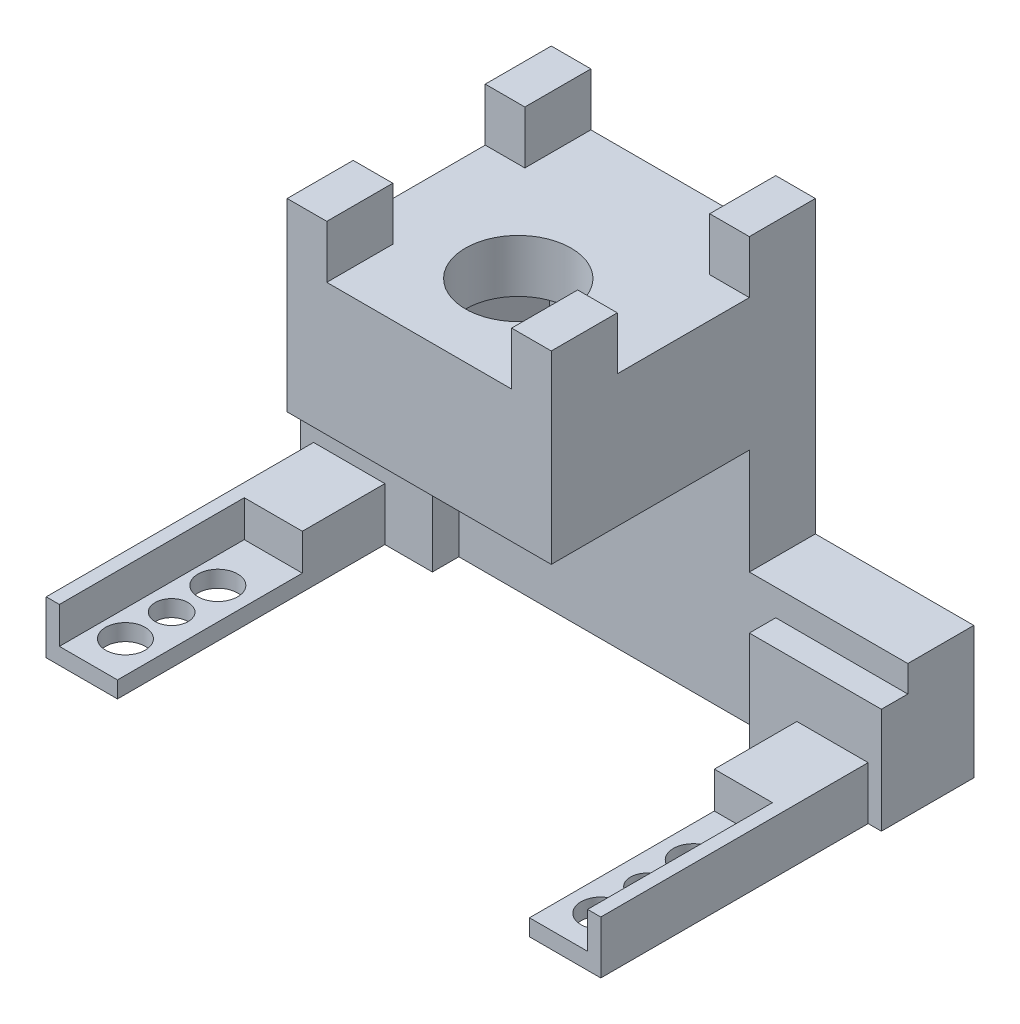
SolidWorks part; units mm, degrees
ref_plane "Front Plane" through (0, 0, 0) normal (0, 0, 1) x (1, 0, 0)
ref_plane "Top Plane" through (0, 0, 0) normal (0, 1, 0) x (1, 0, 0)
ref_plane "Right Plane" through (0, 0, 0) normal (1, 0, 0) x (0, 0, -1)
sketch "Sketch1" plane through (0, 0, 0) normal (0, 0, 1) x (1, 0, 0)
  line L0 (0, 0) -> (44, 0)
  line L5 (44, 0) -> (44, 10)
  line L6 (44, 10) -> (32, 10)
  line L7 (32, 10) -> (32, 28)
  line L8 (32, 28) -> (12, 28)
  line L9 (12, 28) -> (12, 10)
  line L10 (12, 10) -> (0, 10)
  line L11 (0, 10) -> (0, 0)
  point P6 (22, 28)
  point P10 (22, 0)
  dimension "D1" = 20
  dimension "D2" = 44
  dimension "D3" = 10
  dimension "D4" = 18
extrude "Boss-Extrude1" add sketch "Sketch1" along normal blind 5
sketch "Sketch2" plane through (0, 0, 5) normal (0, 0, 1) x (1, 0, 0)
  line L1 (44, 0) -> (34, 0)
  line L2 (44, 0) -> (44, 8)
  line L3 (44, 8) -> (34, 8)
  line L4 (34, 0) -> (34, 8)
  line L5 (0, 0) -> (10, 0)
  line L6 (0, 0) -> (0, 8)
  line L7 (0, 8) -> (10, 8)
  line L8 (10, 0) -> (10, 8)
  dimension "D1" = 10
  dimension "D2" = 8
extrude "Boss-Extrude2" add sketch "Sketch2" along normal blind 2
sketch "Sketch3" plane through (0, 0, 7) normal (0, 0, 1) x (1, 0, 0)
  line L0 (34, 0) -> (44, 0) construction
  line L1 (43, 0) -> (37.6, 0)
  line L2 (43, 0) -> (43, 4)
  line L3 (43, 4) -> (37.6, 4)
  line L4 (37.6, 0) -> (37.6, 4)
  line L5 (0, 0) -> (10, 0) construction
  line L6 (6.4, 0) -> (1, 0)
  line L7 (6.4, 0) -> (6.4, 4)
  line L8 (6.4, 4) -> (1, 4)
  line L9 (1, 0) -> (1, 4)
  line L11 (37.6, 4) -> (42, 4)
  line L12 (37.6, 4) -> (37.6, 1.25)
  line L13 (37.6, 1.25) -> (42, 1.25)
  line L14 (44, 0) -> (44, 8)
  line L15 (44, 8) -> (34, 8)
  line L16 (34, 8) -> (34, 0)
  line L17 (34, 0) -> (44, 0)
  line L18 (44, 0) -> (44, 8)
  line L19 (44, 8) -> (34, 8)
  line L20 (34, 8) -> (34, 0)
  line L21 (34, 0) -> (44, 0)
  line L22 (0, 8) -> (0, 0)
  line L23 (0, 0) -> (10, 0)
  line L24 (10, 0) -> (10, 8)
  line L25 (10, 8) -> (0, 8)
  line L26 (0, 8) -> (0, 0)
  line L27 (0, 0) -> (10, 0)
  line L28 (10, 0) -> (10, 8)
  line L29 (10, 8) -> (0, 8)
  line L30 (42, 4) -> (42, 1.25)
  line L31 (6.4, 4) -> (2, 4)
  line L32 (6.4, 4) -> (6.4, 1.25)
  line L33 (6.4, 1.25) -> (2, 1.25)
  line L34 (2, 4) -> (2, 1.25)
  line M18 (34, 0) -> (44, 0)
  dimension "D3" = 1
  dimension "D4" = 1
  dimension "D5" = 4
  dimension "D6" = 5.4
  dimension "D7" = 1.25
  dimension "D8" = 1
  dimension "D1" = 0
  dimension "D2" = 0
extrude "Boss-Extrude3" add sketch "Sketch3" along normal blind 20.25 contours L9 L6 L7 L8 | L3 L30 L13 L4 L2 M18
sketch "Sketch4" plane through (0, 1.25, 0) normal (0, 1, 0) x (1, 0, 0)
  line L4 (6.4, -7) -> (2, -7)
  line L5 (2, -7) -> (2, -27.25)
  line L6 (2, -27.25) -> (6.4, -27.25)
  line L7 (6.4, -27.25) -> (6.4, -7)
  line L8 (6.4, -7) -> (2, -7)
  line L9 (2, -7) -> (2, -27.25)
  line L10 (2, -27.25) -> (6.4, -27.25)
  line L11 (6.4, -27.25) -> (6.4, -7)
  line L16 (42, -7) -> (37.6, -7)
  line L17 (37.6, -7) -> (37.6, -27.25)
  line L18 (37.6, -27.25) -> (42, -27.25)
  line L19 (42, -27.25) -> (42, -7)
  line L20 (42, -7) -> (37.6, -7)
  line L21 (37.6, -7) -> (37.6, -27.25)
  line L22 (37.6, -27.25) -> (42, -27.25)
  line L23 (42, -27.25) -> (42, -7)
  circle A0 centre (4, -24.25) radius 1.5
  circle A1 centre (4, -20.75) radius 1.25
  circle A2 centre (4, -17.25) radius 1.5
  circle A3 centre (40, -17.25) radius 1.5
  circle A4 centre (40, -20.75) radius 1.25
  circle A5 centre (40, -24.25) radius 1.5
  dimension "D1" = 0
  dimension "D2" = 0
  dimension "D4" = 3
  dimension "D5" = 2.5
  dimension "D3" = 2.4
  dimension "D6" = 7
  dimension "D7" = 3.5
  dimension "D8" = 3
  dimension "D9" = 2.4
extrude "Cut-Extrude1" cut sketch "Sketch4" against normal through all contours A4 | A5 | A0 | A2 | A1 | A3
sketch "Sketch6" plane through (0, 0, 7) normal (0, 0, 1) x (1, 0, 0)
  line L0 (2, 4) -> (6.4, 4)
  line L1 (6.4, 4) -> (6.4, 1.25)
  line L2 (42, 4) -> (37.6, 4)
  line L3 (37.6, 4) -> (37.6, 1.25)
  line L10 (0, 0) -> (1, 0)
  line L11 (1, 0) -> (1, 4)
  line L12 (1, 4) -> (2, 4)
  line L13 (2, 4) -> (2, 1.25)
  line L14 (2, 1.25) -> (6.4, 1.25)
  line L15 (6.4, 1.25) -> (6.4, 0)
  line L16 (6.4, 0) -> (10, 0)
  line L17 (10, 0) -> (10, 8)
  line L18 (10, 8) -> (0, 8)
  line L19 (0, 8) -> (0, 0)
  line L20 (0, 0) -> (1, 0)
  line L21 (1, 0) -> (1, 4)
  line L22 (1, 4) -> (2, 4)
  line L23 (2, 4) -> (2, 1.25)
  line L24 (2, 1.25) -> (6.4, 1.25)
  line L25 (6.4, 1.25) -> (6.4, 0)
  line L26 (6.4, 0) -> (10, 0)
  line L27 (10, 0) -> (10, 8)
  line L28 (10, 8) -> (0, 8)
  line L29 (0, 8) -> (0, 0)
  line L32 (37.6, 0) -> (37.6, 1.25)
  line L33 (37.6, 1.25) -> (42, 1.25)
  line L34 (42, 1.25) -> (42, 4)
  line L35 (42, 4) -> (43, 4)
  line L36 (43, 4) -> (43, 0)
  line L37 (43, 0) -> (44, 0)
  line L38 (44, 0) -> (44, 8)
  line L39 (44, 8) -> (34, 8)
  line L40 (34, 8) -> (34, 0)
  line L41 (34, 0) -> (37.6, 0)
  line L42 (37.6, 0) -> (37.6, 1.25)
  line L43 (37.6, 1.25) -> (42, 1.25)
  line L44 (42, 1.25) -> (42, 4)
  line L45 (42, 4) -> (43, 4)
  line L46 (43, 4) -> (43, 0)
  line L47 (43, 0) -> (44, 0)
  line L48 (44, 0) -> (44, 8)
  line L49 (44, 8) -> (34, 8)
  line L50 (34, 8) -> (34, 0)
  line L51 (34, 0) -> (37.6, 0)
  line M24 (2, 4) -> (2, 1.25)
  line M25 (2, 1.25) -> (6.4, 1.25)
  dimension "D1" = 0
  dimension "D2" = 0
extrude "Boss-Extrude4" add sketch "Sketch6" along normal blind 6.25 contours L1 L0 M24 M25 | L43 L44 L2 L3
sketch "Sketch7" plane through (0, 0, 5) normal (0, 0, 1) x (1, 0, 0)
  line L0 (12, 18) -> (32, 18)
  line L12 (0, 8) -> (10, 8)
  line L13 (10, 8) -> (10, 0)
  line L14 (10, 0) -> (34, 0)
  line L15 (34, 0) -> (34, 8)
  line L16 (34, 8) -> (44, 8)
  line L17 (44, 8) -> (44, 10)
  line L18 (44, 10) -> (32, 10)
  line L19 (32, 10) -> (32, 28)
  line L20 (32, 28) -> (12, 28)
  line L21 (12, 28) -> (12, 10)
  line L22 (12, 10) -> (0, 10)
  line L23 (0, 10) -> (0, 8)
  line L24 (0, 8) -> (10, 8)
  line L25 (10, 8) -> (10, 0)
  line L26 (10, 0) -> (34, 0)
  line L27 (34, 0) -> (34, 8)
  line L28 (34, 8) -> (44, 8)
  line L29 (44, 8) -> (44, 10)
  line L30 (44, 10) -> (32, 10)
  line L31 (32, 10) -> (32, 28)
  line L32 (32, 28) -> (12, 28)
  line L33 (12, 28) -> (12, 10)
  line L34 (12, 10) -> (0, 10)
  line L35 (0, 10) -> (0, 8)
  line M21 (32, 10) -> (32, 28)
  line M22 (32, 28) -> (12, 28)
  line M23 (12, 28) -> (12, 10)
  dimension "D2" = 10
  dimension "D1" = 0
extrude "Boss-Extrude5" add sketch "Sketch7" along normal blind 15 contours L0 M23 M21 M22
sketch "Sketch8" plane through (0, 18, 0) normal (0, -1, 0) x (1, 0, 0)
  line L1 (18.7524, 18.125) -> (15.5048, 12.5)
  line L2 (15.5048, 12.5) -> (18.7524, 6.875)
  line L3 (18.7524, 6.875) -> (25.2476, 6.875)
  line L4 (12, 5) -> (32, 5)
  line L5 (32, 5) -> (32, 20)
  line L6 (32, 20) -> (12, 20)
  line L7 (12, 20) -> (12, 5)
  line L8 (12, 5) -> (32, 5)
  line L9 (32, 5) -> (32, 20)
  line L10 (32, 20) -> (12, 20)
  line L11 (12, 20) -> (12, 5)
  line L12 (25.2476, 6.875) -> (28.4952, 12.5)
  line L13 (28.4952, 12.5) -> (25.2476, 18.125)
  line L14 (25.2476, 18.125) -> (18.7524, 18.125)
  circle A0 centre (22, 12.5) radius 5.625 construction
  point P4 (32, 12.5)
  point P13 (22, 20)
  dimension "D2" = 11.25
  dimension "D1" = 0
extrude "Cut-Extrude2" cut sketch "Sketch8" against normal blind 6 contours L13 L14 L1 L2 L3 L12
sketch "Sketch9" plane through (0, 24, 0) normal (0, -1, 0) x (1, 0, 0)
  line L6 (28.4952, 12.5) -> (25.2476, 18.125)
  line L7 (25.2476, 18.125) -> (18.7524, 18.125)
  line L8 (18.7524, 18.125) -> (15.5048, 12.5)
  line L9 (15.5048, 12.5) -> (18.7524, 6.875)
  line L10 (18.7524, 6.875) -> (25.2476, 6.875)
  line L11 (25.2476, 6.875) -> (28.4952, 12.5)
  line L12 (28.4952, 12.5) -> (25.2476, 18.125)
  line L13 (25.2476, 18.125) -> (18.7524, 18.125)
  line L14 (18.7524, 18.125) -> (15.5048, 12.5)
  line L15 (15.5048, 12.5) -> (18.7524, 6.875)
  line L16 (18.7524, 6.875) -> (25.2476, 6.875)
  line L17 (25.2476, 6.875) -> (28.4952, 12.5)
  circle A0 centre (22, 12.5) radius 4
  point P6 (22, 18.125)
  dimension "D2" = 8
  dimension "D1" = 0
extrude "Cut-Extrude3" cut sketch "Sketch9" against normal through all contours A0
sketch "Sketch10" plane through (0, 28, 0) normal (0, 1, 0) x (1, 0, 0)
  line L0 (32, -5) -> (29, -5)
  line L1 (29, -5) -> (29, 0)
  line L2 (12, -5) -> (15, -5)
  line L3 (15, -5) -> (15, 0)
  line L4 (32, 0) -> (12, 0)
  line L5 (12, 0) -> (12, -20)
  line L6 (12, -20) -> (32, -20)
  line L7 (32, -20) -> (32, 0)
  line L8 (32, 0) -> (12, 0)
  line L9 (12, 0) -> (12, -20)
  line L10 (12, -20) -> (32, -20)
  line L11 (32, -20) -> (32, 0)
  line L12 (12, -15) -> (15, -15)
  line L13 (15, -15) -> (15, -20)
  line L14 (32, -15) -> (29, -15)
  line L15 (29, -15) -> (29, -20)
  line M6 (32, 0) -> (12, 0)
  line M7 (12, 0) -> (12, -20)
  line M8 (12, -20) -> (32, -20)
  line M9 (32, -20) -> (32, 0)
  dimension "D2" = 3
  dimension "D3" = 5
  dimension "D1" = 0
extrude "Boss-Extrude6" add sketch "Sketch10" along normal blind 4 contours L1 L0 M9 M6 | L14 L15 M8 M9 | L2 L3 M6 M7 | L13 L12 L9 M8
equation "\"D4@Sketch3\"=\"D3@Sketch3\""
equation "\"D3@Sketch4\"=\"D4@Sketch4\"/2+0.9"
equation "\"D6@Sketch4\"=10-\"D4@Sketch4\""
equation "\"D7@Sketch4\"=\"D6@Sketch4\"/2"
equation "\"D9@Sketch4\"=\"D3@Sketch4\""
